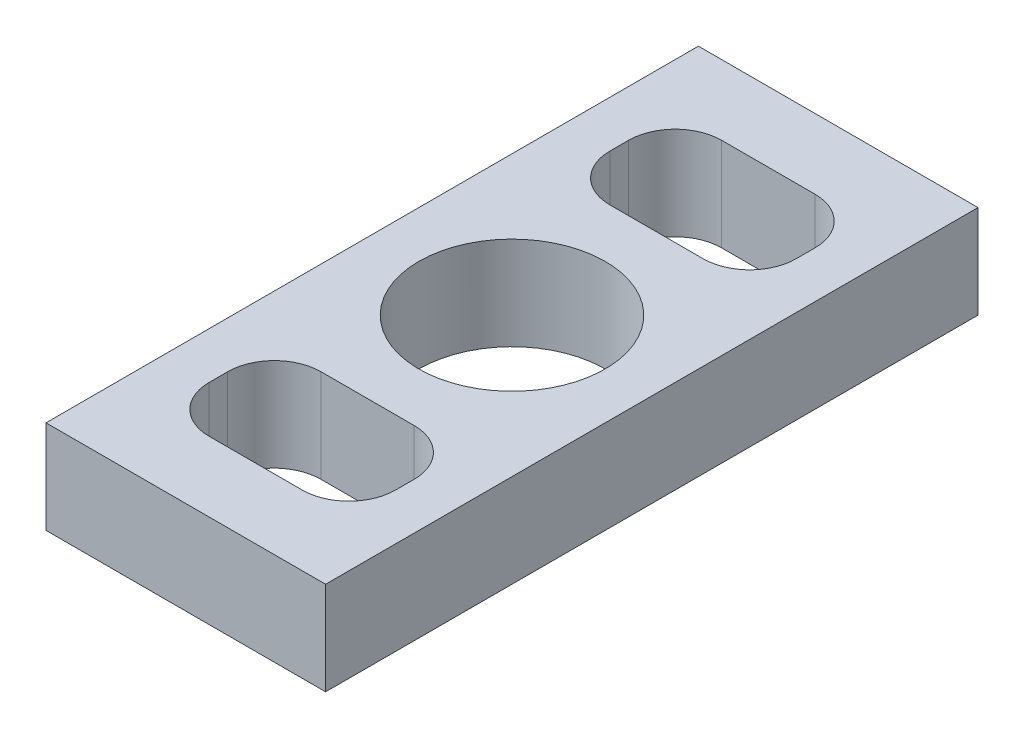
SolidWorks part; units mm, degrees
material "6061 Alloy"
ref_plane "Front Plane" through (0, 0, 0) normal (0, 0, 1) x (1, 0, 0)
ref_plane "Top Plane" through (0, 0, 0) normal (0, 1, 0) x (1, 0, 0)
ref_plane "Right Plane" through (0, 0, 0) normal (1, 0, 0) x (0, 0, -1)
sketch "Sketch1" plane through (0, 0, 0) normal (0, 0, 1) x (1, 0, 0)
  line L1 (-24.7431, 6.131) -> (13.3569, 6.131)
  line L2 (-24.7431, 6.131) -> (-24.7431, -6.569)
  line L3 (-24.7431, -6.569) -> (13.3569, -6.569)
  line L4 (13.3569, 6.131) -> (13.3569, -6.569)
  dimension "D1" = 12.7
  dimension "D2" = 38.1
extrude "Boss-Extrude1" add sketch "Sketch1" along normal blind 88.9
sketch "Sketch2" plane through (0, 6.131, 0) normal (0, 1, 0) x (1, 0, 0)
  line L0 (13.3569, 0) -> (-24.7431, 0) construction
  line L1 (13.3569, -88.9) -> (13.3569, 0) construction
  circle A0 centre (-5.6931, -44.45) radius 12.7
  dimension "D3" = 25.4
  dimension "D1" = 44.45
  dimension "D2" = 19.05
extrude "Cut-Extrude1" cut sketch "Sketch2" against normal blind 88.9
sketch "Sketch3" plane through (0, 6.131, 0) normal (0, 1, 0) x (1, 0, 0)
  line L0 (13.3569, 0) -> (-24.7431, 0) construction
  line L1 (-18.3931, -9.525) -> (7.0069, -9.525)
  line L2 (-18.3931, -9.525) -> (-18.3931, -24.765)
  line L3 (-18.3931, -24.765) -> (7.0069, -24.765)
  line L4 (7.0069, -9.525) -> (7.0069, -24.765)
  line L5 (-18.3931, -79.375) -> (7.0069, -79.375)
  line L6 (-18.3931, -79.375) -> (-18.3931, -64.135)
  line L7 (-18.3931, -64.135) -> (7.0069, -64.135)
  line L8 (7.0069, -79.375) -> (7.0069, -64.135)
  line L9 (13.3569, -88.9) -> (-24.7431, -88.9) construction
  line L10 (-24.7431, -88.9) -> (-24.7431, 0) construction
  dimension "D1" = 9.525
  dimension "D2" = 9.525
  dimension "D3" = 15.24
  dimension "D4" = 15.24
  dimension "D5" = 25.4
  dimension "D6" = 6.35
extrude "Cut-Extrude2" cut sketch "Sketch3" against normal blind 12.7
sketch "Sketch4" plane through (0, -6.569, 0) normal (0, -1, 0) x (1, 0, 0)
  line L0 (13.3569, 88.9) -> (13.3569, 0) construction
  line L1 (7.0069, 79.375) -> (-18.3931, 79.375)
  line L2 (7.0069, 79.375) -> (7.0069, 64.135)
  line L3 (7.0069, 64.135) -> (-18.3931, 64.135)
  line L4 (-18.3931, 79.375) -> (-18.3931, 64.135)
  line L5 (-18.3931, 24.765) -> (7.0069, 24.765)
  line L6 (-18.3931, 24.765) -> (-18.3931, 9.525)
  line L7 (-18.3931, 9.525) -> (7.0069, 9.525)
  line L8 (7.0069, 24.765) -> (7.0069, 9.525)
  line L9 (-24.7431, 88.9) -> (13.3569, 88.9) construction
  line L10 (-24.7431, 0) -> (13.3569, 0) construction
  dimension "D1" = 6.35
  dimension "D2" = 9.525
  dimension "D3" = 25.4
  dimension "D4" = 9.525
  dimension "D5" = 15.24
  dimension "D6" = 15.24
extrude "Cut-Extrude3" [suppressed] cut sketch "Sketch4" against normal blind 3.175
fillet "Fillet1" radius 6.35 8 edges at (7.0069, -0.219, 24.765) (-18.3931, -0.219, 24.765) (-18.3931, -0.219, 9.525) (7.0069, -0.219, 9.525) (7.0069, -0.219, 64.135) (7.0069, -0.219, 79.375) (-18.3931, -0.219, 79.375) (-18.3931, -0.219, 64.135)
